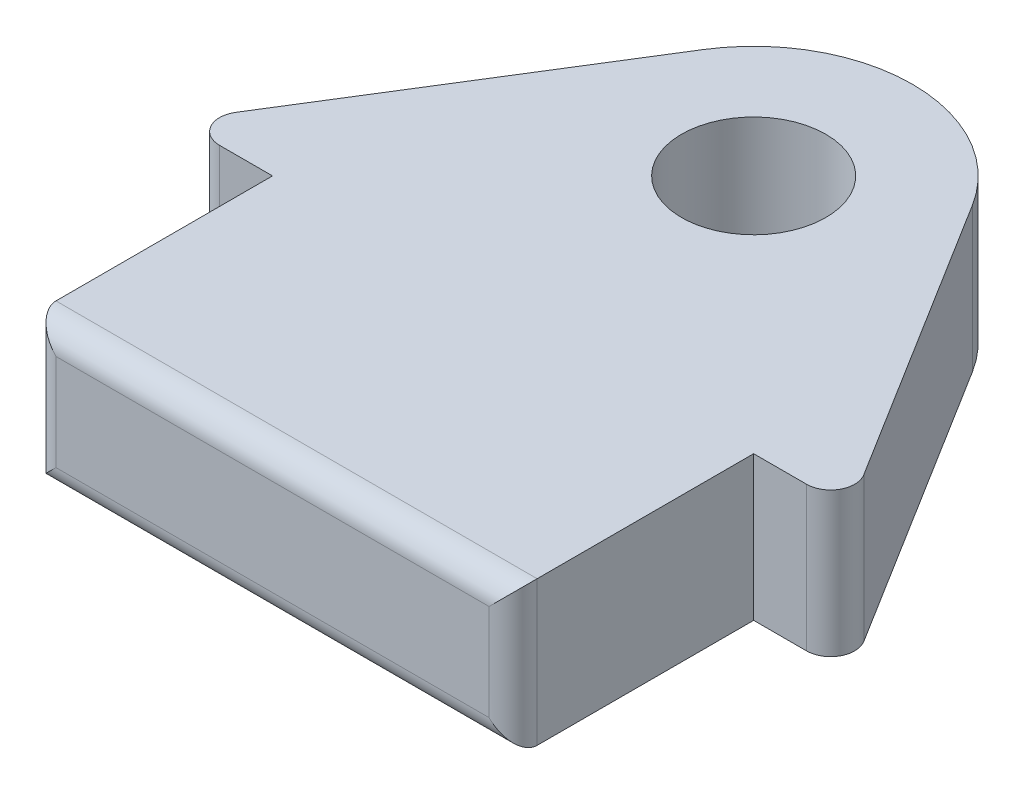
SolidWorks part; units mm, degrees
ref_plane "Front Plane" through (0, 0, 0) normal (0, 0, 1) x (1, 0, 0)
ref_plane "Top Plane" through (0, 0, 0) normal (0, 1, 0) x (1, 0, 0)
ref_plane "Right Plane" through (0, 0, 0) normal (1, 0, 0) x (0, 0, -1)
sketch "Sketch1" plane through (0, 0, 0) normal (0, 1, 0) x (1, 0, 0)
  line L0 (-8.89, -6.35) -> (-6.35, -6.35)
  line L1 (8.89, -6.35) -> (3.5579, 2.215)
  line L2 (-8.89, -6.35) -> (-3.5579, 2.215)
  line L3 (0, 0) -> (0, -12.7) construction
  line L4 (-6.35, -6.35) -> (-6.35, -12.7)
  line L5 (-6.35, -12.7) -> (6.35, -12.7)
  line L6 (6.35, -12.7) -> (6.35, -6.35)
  line L7 (6.35, -6.35) -> (8.89, -6.35)
  circle A0 centre (0, 0) radius 1.905
  arc A1 (3.5579, 2.215) -> (-3.5579, 2.215) centre (0, 0) ccw
  dimension "D1" = 12.7
  dimension "D2" = 4.191
  dimension "D6" = 3.81
  dimension "D3" = 17.78
  dimension "D4" = 6.35
  dimension "D5" = 12.7
extrude "Boss-Extrude1" add sketch "Sketch1" along normal blind 3.81
fillet "Fillet1" radius 0.635 6 edges at (8.89, 1.905, 6.35) (6.35, 1.905, 12.7) (-6.35, 1.905, 12.7) (-8.89, 1.905, 6.35) (0, 3.81, 12.7) (0, 0, 12.7)
